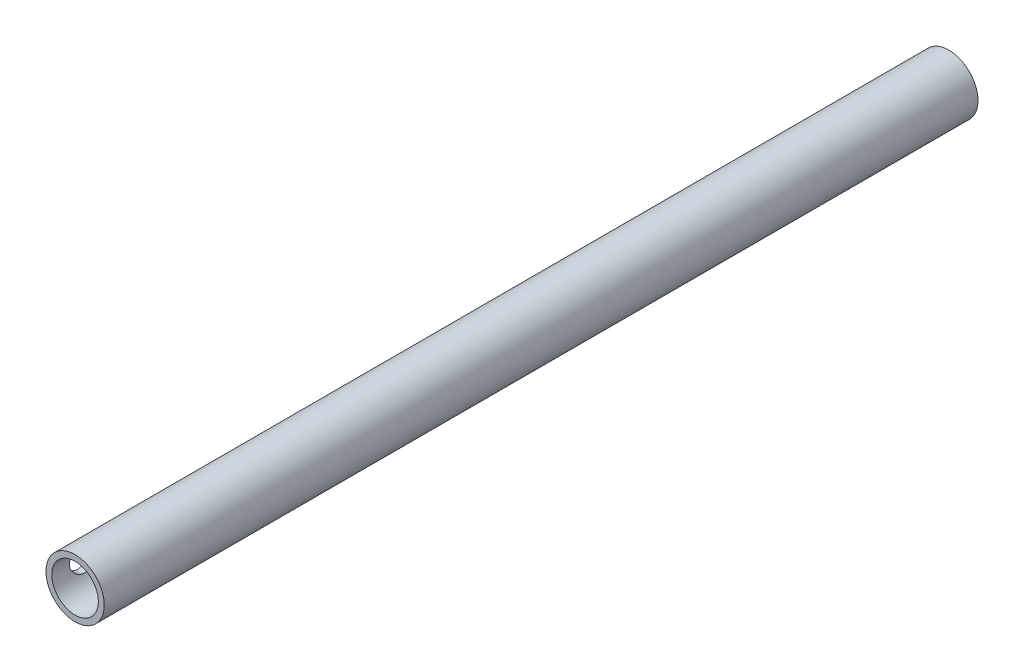
SolidWorks part; units mm, degrees
ref_plane "Front Plane" through (0, 0, 0) normal (0, 0, 1) x (1, 0, 0)
ref_plane "Top Plane" through (0, 0, 0) normal (0, 1, 0) x (1, 0, 0)
ref_plane "Right Plane" through (0, 0, 0) normal (1, 0, 0) x (0, 0, -1)
sketch "Sketch1" plane through (0, 0, 0) normal (0, 0, 1) x (1, 0, 0)
  circle A1 centre (0, 0) radius 50
  circle A2 centre (0, 0) radius 40
  dimension "D1" = 10
extrude "Boss-Extrude1" add sketch "Sketch1" along normal blind 1500
sketch "Sketch2" plane through (0, 0, 0) normal (1, 0, 0) x (0, 0, -1)
  line L0 (-1500, 50) -> (-1500, -50) construction
  circle A0 centre (-1450, 0) radius 20
  circle A1 centre (-1350, 0) radius 20
  circle A2 centre (-1250, 0) radius 20
  circle A3 centre (-1150, 0) radius 20
  circle A4 centre (-1050, 0) radius 20
  circle A5 centre (-950, 0) radius 20
  circle A6 centre (-850, 0) radius 20
  circle A7 centre (-750, 0) radius 20
  circle A8 centre (-650, 0) radius 20
  circle A9 centre (-550, 0) radius 20
  circle A10 centre (-450, 0) radius 20
  circle A11 centre (-350, 0) radius 20
  circle A12 centre (-250, 0) radius 20
  circle A13 centre (-150, 0) radius 20
  circle A14 centre (-50, 0) radius 20
  dimension "D1" = 50
  dimension "25" = 40
  dimension "D2" = 15
extrude "Cut-Extrude1" cut sketch "Sketch2" against normal blind 100
